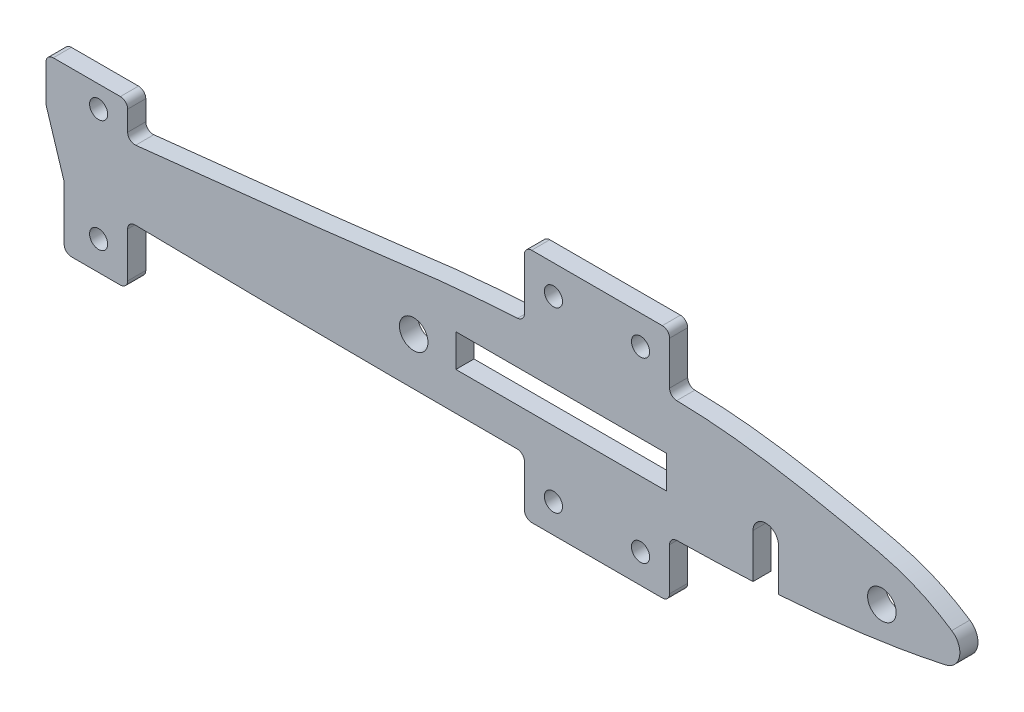
SolidWorks part; units mm, degrees
material "Carbon/Foam Panel"
ref_plane "Front Plane" through (0, 0, 0) normal (0, 0, 1) x (1, 0, 0)
ref_plane "Top Plane" through (0, 0, 0) normal (0, 1, 0) x (1, 0, 0)
ref_plane "Right Plane" through (0, 0, 0) normal (1, 0, 0) x (0, 0, -1)
sketch "Sketch1" plane through (0, 0, 0) normal (0, 0, 1) x (1, 0, 0)
  ellipse E1 centre (137.6249, -20.0426) end of major axis (189.6794, -20.0426) minor radius 48.2641 (175.2698, 13.2914) -> (153.373, 25.9598) ccw construction
  spline S0 degree 3 poles (-276.1301, 8.6931) (-231.4597, 13.8922) (-160.6069, 22.0458) (-55.2186, 32.8482) (-5.4847, 39.5878) (20.2948, 40.7341) (52.2153, 43.3112) (77.4334, 43.8548) (107.6579, 39.591) (131.1314, 34.7665) (149.4992, 30.2941) (163.4187, 23.0591) (171.5303, 16.9219) (175.2698, 13.2914) knots 0 0 0 0 0.247404 0.462109 0.504395 0.627983 0.653402 0.743134 0.818761 0.882434 0.92418 0.960505 1 1 1 1
  spline S4 degree 3 poles (-276.1301, 8.6931) (-174.261, 0.9112) (-23.6694, 0.6839) (127.5151, 0.6814) (175.2698, 13.2914) knots 0 0 0 0 0.676464 1 1 1 1
extrude "Boss-Extrude1" add sketch "Sketch1" along normal blind 6.35 contours S4 S0
fillet "Fillet1" radius 6.35 1 edges at (175.2698, 13.2914, 3.175)
sketch "Sketch2" plane through (0, 0, 0) normal (0, 1, 0) x (1, 0, 0)
  line L0 (164.696, 0) -> (-276.1301, 0) construction
  line L1 (-174.5301, 0) -> (-123.7301, 0)
  line L2 (-174.5301, 0) -> (-174.5301, -6.35)
  line L3 (-174.5301, -6.35) -> (-123.7301, -6.35)
  line L4 (-123.7301, 0) -> (-123.7301, -6.35)
  line L5 (-276.1301, -6.35) -> (164.696, -6.35) construction
  line L6 (-276.1301, -6.35) -> (-276.1301, 0) construction
  line L7 (167.5377, -6.35) -> (167.5377, 0) construction
  line L8 (15.1377, 0) -> (65.9377, 0)
  line L9 (15.1377, 0) -> (15.1377, -6.35)
  line L10 (15.1377, -6.35) -> (65.9377, -6.35)
  line L11 (65.9377, 0) -> (65.9377, -6.35)
  dimension "D1" = 50.8
  dimension "D2" = 101.6
  dimension "D3" = 50.8
  dimension "D4" = 101.6
extrude "Boss-Extrude2" add sketch "Sketch2" along normal mid plane 38.1
sketch "Sketch3" plane through (0, 0, 0) normal (0, 1, 0) x (1, 0, 0)
  line L0 (164.696, 0) -> (-276.1301, 0) construction
  line L1 (-174.5301, 0) -> (-123.7301, 0)
  line L2 (-174.5301, 0) -> (-174.5301, -6.35)
  line L3 (-174.5301, -6.35) -> (-123.7301, -6.35)
  line L4 (-123.7301, 0) -> (-123.7301, -6.35)
  line L5 (-276.1301, -6.35) -> (164.696, -6.35) construction
  line L6 (-276.1301, -6.35) -> (-276.1301, 0) construction
  dimension "D1" = 50.8
  dimension "D2" = 101.6
extrude "Boss-Extrude3" add sketch "Sketch3" along normal blind 38.1
sketch "Sketch4" plane through (0, 0, 0) normal (0, 1, 0) x (1, 0, 0)
  line L0 (164.696, 0) -> (-123.7301, 0) construction
  line L1 (15.1377, 0) -> (65.9377, 0)
  line L2 (15.1377, 0) -> (15.1377, -6.35)
  line L3 (15.1377, -6.35) -> (65.9377, -6.35)
  line L4 (65.9377, 0) -> (65.9377, -6.35)
  line L5 (-123.7301, -6.35) -> (164.696, -6.35) construction
  line L6 (167.5377, -6.35) -> (167.5377, 0) construction
  dimension "D1" = 50.8
  dimension "D2" = 101.6
extrude "Boss-Extrude4" add sketch "Sketch4" along normal blind 63.5
fillet "Fillet2" radius 2.54 16 edges at (65.9377, 0.8824, 3.175) (15.1377, 0.7153, 3.175) (-123.7301, 1.8095, 3.175) (-174.5301, 3.1849, 3.175) (-174.5301, 20.2643, 3.175) (-123.7301, 25.7349, 3.175) (15.1377, 40.5759, 3.175) (65.9377, 43.3229, 3.175) (65.9377, -19.05, 3.175) (15.1377, -19.05, 3.175) (-174.5301, -19.05, 3.175) (-123.7301, -19.05, 3.175) (-174.5301, 38.1, 3.175) (-123.7301, 38.1, 3.175) (65.9377, 63.5, 3.175) (15.1377, 63.5, 3.175)
sketch "Sketch5" plane through (0, 0, 0) normal (0, 0, 1) x (1, 0, 0)
  line L0 (64.8038, 25.527) -> (-8.8562, 25.527)
  line L1 (-8.8562, 25.527) -> (-8.8562, 14.097)
  line L2 (64.8038, 14.097) -> (-8.8562, 14.097)
  line L3 (60.9938, 25.527) -> (60.9938, 14.097) construction
  line L4 (64.8038, 25.527) -> (64.8038, 14.097)
  line L5 (64.8038, 19.812) -> (-8.8562, 19.812) construction
  line L6 (-7.5862, 25.527) -> (-7.5862, 14.097) construction
  line L7 (27.9738, 25.527) -> (27.9738, 14.097) construction
  line L8 (140.2418, 17.41) -> (167.4616, 17.41) construction
  line L10 (140.2418, 17.41) -> (-23.6136, 17.41) construction
  line L11 (3.4925, 0) -> (-3.4925, 0) construction
  circle A0 centre (140.2418, 17.41) radius 5
  circle A1 centre (-23.6136, 17.41) radius 5
  arc A2 (162.5427, 10.2263) -> (164.696, 21.7229) centre (161.1877, 16.43) ccw construction
  dimension "D5" = 10
  dimension "D6" = 1.27
  dimension "D8" = 10
  dimension "D1" = 11.43
  dimension "D2" = 68.58
  dimension "D3" = 79.248
  dimension "D4" = 3.81
  dimension "D7" = 163.8554
  dimension "D9" = 27.2198
  dimension "D10" = 17.41
  dimension "D11" = 19.812
extrude "Cut-Extrude3" cut sketch "Sketch5" along normal through all
sketch "Sketch6" plane through (0, 0, 0) normal (0, 0, 1) x (1, 0, 0)
  line L0 (63.3977, 63.5) -> (17.6777, 63.5) construction
  line L1 (65.9377, 60.96) -> (65.9377, 45.8341) construction
  line L2 (15.1377, 60.96) -> (15.1377, 42.9544) construction
  line L3 (63.3977, -19.05) -> (17.6777, -19.05) construction
  line L4 (-123.7301, 35.56) -> (-123.7301, 28.5592) construction
  line L5 (-126.2701, 38.1) -> (-171.9901, 38.1) construction
  line L6 (-174.5301, 35.56) -> (-174.5301, 22.5401) construction
  circle A0 centre (55.7777, 53.34) radius 3.175
  circle A1 centre (25.2977, 53.34) radius 3.175
  circle A2 centre (55.7777, -8.89) radius 3.175
  circle A3 centre (25.2977, -8.89) radius 3.175
  circle A4 centre (-133.8901, 30.48) radius 3.175
  circle A5 centre (-164.3701, 30.48) radius 3.175
  circle A6 centre (-133.8901, -8.89) radius 3.175
  circle A7 centre (-164.3701, -8.89) radius 3.175
  dimension "D1" = 6.35
  dimension "D2" = 6.35
  dimension "D7" = 6.35
  dimension "D8" = 6.35
  dimension "D11" = 6.35
  dimension "D14" = 6.35
  dimension "D17" = 6.35
  dimension "D18" = 6.35
  dimension "D3" = 10.16
  dimension "D4" = 10.16
  dimension "D5" = 10.16
  dimension "D6" = 10.16
  dimension "D9" = 10.16
  dimension "D10" = 10.16
  dimension "D12" = 10.16
  dimension "D13" = 7.62
  dimension "D15" = 10.16
  dimension "D16" = 7.62
extrude "Cut-Extrude4" cut sketch "Sketch6" along normal through all
sketch "Sketch8" plane through (0, 0, 0) normal (0, 0, -1) x (-1, 0, 0)
  line L0 (152.3051, 22.653) -> (152.3051, 35.56)
  line L1 (145.9551, 2.4306) -> (145.9551, -16.51)
  line L2 (152.3051, 22.653) -> (145.9551, 2.4306)
  line L3 (120.9216, 26.0334) -> (176.792, 20.0154) construction
  line L4 (121.1408, 1.7583) -> (176.9798, 3.2711) construction
  line L5 (126.2701, -19.05) -> (171.9901, -19.05) construction
  line L6 (126.2701, 38.1) -> (171.9901, 38.1) construction
  line L7 (123.7301, 35.56) -> (123.7301, 28.5592) construction
  line L8 (123.7301, -0.7812) -> (123.7301, -16.51) construction
  arc A0 (152.3051, 35.56) -> (149.7651, 38.1) centre (149.7651, 35.56) ccw
  arc A1 (145.9551, -16.51) -> (143.4151, -19.05) centre (143.4151, -16.51) cw
  line M51 (126.2701, -19.05) -> (171.9901, -19.05)
  arc M52 (171.9901, -19.05) -> (174.5301, -16.51) centre (171.9901, -16.51) ccw
  line M53 (174.5301, -16.51) -> (174.5301, 0.7327)
  arc M54 (174.5301, 0.7327) -> (176.9798, 3.2711) centre (177.0701, 0.7327) cw
  spline M55 degree 3 poles (-175.2698, 13.2914) (-127.5151, 0.6814) (23.6694, 0.6839) (174.261, 0.9112) (276.1301, 8.6931) knots 0 0 0 0 0.323536 1 1 1 1 only from (176.9798, 3.2711) to (276.1301, 8.6931)
  spline M56 degree 3 poles (276.1301, 8.6931) (231.4597, 13.8922) (160.6069, 22.0458) (55.2186, 32.8482) (5.4847, 39.5878) (-20.2948, 40.7341) (-52.2153, 43.3112) (-77.4334, 43.8548) (-107.6579, 39.591) (-131.1314, 34.7665) (-149.4992, 30.2941) (-163.4187, 23.0591) (-171.5303, 16.9219) (-175.2698, 13.2914) knots 0 0 0 0 0.247404 0.462109 0.504395 0.627983 0.653402 0.743134 0.818761 0.882434 0.92418 0.960505 1 1 1 1 only from (276.1301, 8.6931) to (176.792, 20.0154)
  arc M57 (176.792, 20.0154) -> (174.5301, 22.5401) centre (177.0701, 22.5401) cw
  line M58 (174.5301, 22.5401) -> (174.5301, 35.56)
  arc M59 (174.5301, 35.56) -> (171.9901, 38.1) centre (171.9901, 35.56) ccw
  line M60 (171.9901, 38.1) -> (126.2701, 38.1)
  circle M83 centre (164.3701, 30.48) radius 3.175
  circle M84 centre (164.3701, -8.89) radius 3.175
  dimension "D4" = 2.54
  dimension "D5" = 2.54
  dimension "D2" = 22.225
  dimension "D1" = 28.575
extrude "Cut-Extrude5" cut sketch "Sketch8" against normal through all contours L0 L2 L1 M51 M52 M53 M54 M55 M56 M57 M58 M59 M60 M83 M84
sketch "Sketch10" plane through (0, 0, 0) normal (0, 0, -1) x (-1, 0, 0)
  line L0 (-95.157, 17.296) -> (-95.157, 1.8106)
  line L1 (-104.047, 17.296) -> (-104.047, 2.3351)
  line L2 (-104.047, 17.296) -> (-95.157, 17.296) construction
  line L3 (-99.602, 17.296) -> (-99.602, 2.056) construction
  arc A0 (-95.157, 17.296) -> (-104.047, 17.296) centre (-99.602, 17.296) ccw
  spline S0 degree 3 poles (558.4122, -1832.231) (405.9314, 1864.4722) (-477.0023, -1893.8833) (-632.0115, 1926.1003) knots -1.026398 -1.026398 -1.026398 -1.026398 2.406265 2.406265 2.406265 2.406265 only from (-68.4327, 0.9238) to (-162.5427, 10.2263) construction
  spline S1 degree 3 poles (-95.157, 1.8106) (-98.1222, 1.9635) (-101.0856, 2.1374) (-104.047, 2.3351) knots 0.821016 0.821016 0.821016 0.821016 0.84073 0.84073 0.84073 0.84073
  dimension "D2" = 4.445
  dimension "D1" = 40.64
  dimension "D3" = 15.24
extrude "Cut-Extrude6" cut sketch "Sketch10" against normal through all
equation "\"D5@Sketch8\"=\"D4@Sketch8\""
